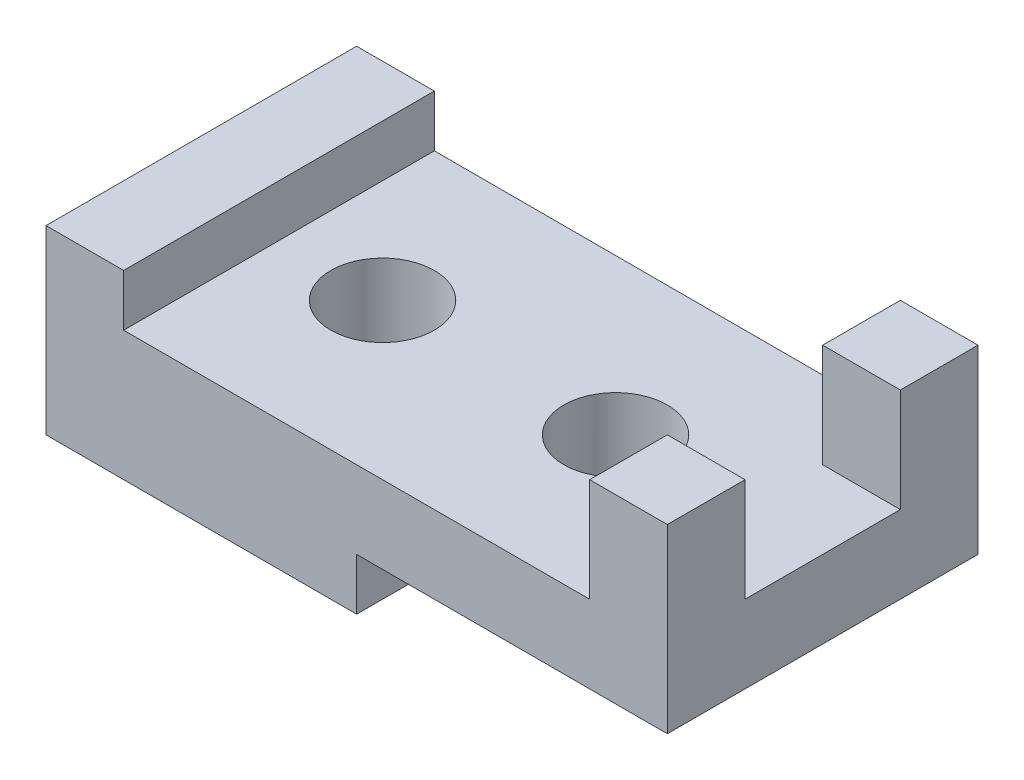
SolidWorks part; units mm, degrees
ref_plane "Front Plane" through (0, 0, 0) normal (0, 0, 1) x (1, 0, 0)
ref_plane "Top Plane" through (0, 0, 0) normal (0, 1, 0) x (1, 0, 0)
ref_plane "Right Plane" through (0, 0, 0) normal (1, 0, 0) x (0, 0, -1)
sketch "Sketch1" plane through (0, 0, 0) normal (0, 1, 0) x (1, 0, 0)
  line L1 (-60, 30) -> (60, 30)
  line L2 (-60, 30) -> (-60, -30)
  line L3 (-60, -30) -> (60, -30)
  line L4 (60, 30) -> (60, -30)
  line L5 (-60, 30) -> (60, -30) construction
  line L6 (-60, -30) -> (60, 30) construction
  point P0 (0, 0)
  dimension "D1" = 120
  dimension "D2" = 60
extrude "Boss-Extrude1" add sketch "Sketch1" along normal blind 25
sketch "Sketch2" plane through (0, 0, 30) normal (0, 0, 1) x (1, 0, 0)
  line L1 (60, 0) -> (0, 0)
  line L2 (60, 0) -> (60, 10)
  line L3 (60, 10) -> (0, 10)
  line L4 (0, 0) -> (0, 10)
  dimension "D1" = 60
  dimension "D2" = 10
extrude "Cut-Extrude1" cut sketch "Sketch2" against normal through all
sketch "Sketch3" plane through (0, 25, 0) normal (0, 1, 0) x (1, 0, 0)
  line L0 (-60, -30) -> (60, -30) construction
  line L1 (-60, 30) -> (-45, 30)
  line L2 (-60, 30) -> (-60, -30)
  line L3 (-60, -30) -> (-45, -30)
  line L4 (-45, 30) -> (-45, -30)
  dimension "D1" = 15
extrude "Boss-Extrude2" add sketch "Sketch3" along normal blind 10
sketch "Sketch4" plane through (0, 25, 0) normal (0, 1, 0) x (1, 0, 0)
  line L1 (60, 30) -> (45, 30)
  line L2 (60, 30) -> (60, 15)
  line L3 (60, 15) -> (45, 15)
  line L4 (45, 30) -> (45, 15)
  dimension "D1" = 15
extrude "Boss-Extrude3" add sketch "Sketch4" along normal blind 20
mirror "Mirror1" about plane through (0, 0, 0) normal (0, 0, 1) of "Boss-Extrude3"
sketch "Sketch5" plane through (0, 25, 0) normal (0, 1, 0) x (1, 0, 0)
  line L0 (-60, 0) -> (60, 0) construction
  line L1 (-60, 30) -> (-60, -30) construction
  line L2 (60, -15) -> (60, 15) construction
  circle A0 centre (-25, 0) radius 10
  point P8 (0, 0)
  point P11 (0, 0)
extrude "Cut-Extrude2" cut sketch "Sketch5" against normal through all
sketch "Sketch6" plane through (0, 25, 0) normal (0, 1, 0) x (1, 0, 0)
  circle A0 centre (20, 0) radius 10
  circle A1 centre (-25, 0) radius 10 construction
extrude "Cut-Extrude3" cut sketch "Sketch6" against normal through all
